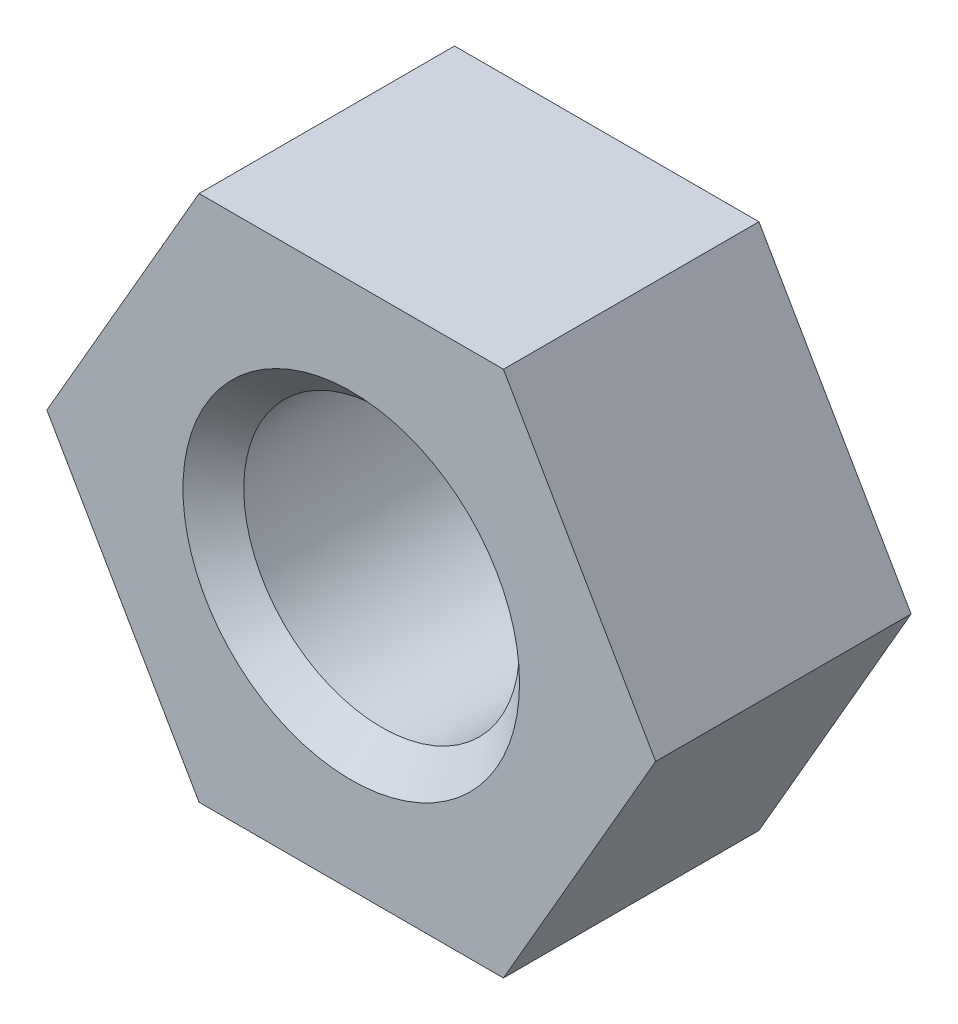
SolidWorks part; units mm, degrees
ref_plane "Front Plane" through (0, 0, 0) normal (0, 0, 1) x (1, 0, 0)
ref_plane "Top Plane" through (0, 0, 0) normal (0, 1, 0) x (1, 0, 0)
ref_plane "Right Plane" through (0, 0, 0) normal (1, 0, 0) x (0, 0, -1)
sketch "Sketch1" plane through (0, 0, 0) normal (0, 0, 1) x (1, 0, 0)
  line L1 (7.5056, 0) -> (3.7528, 6.5)
  line L2 (3.7528, 6.5) -> (-3.7528, 6.5)
  line L3 (-3.7528, 6.5) -> (-7.5056, 0)
  line L4 (-7.5056, 0) -> (-3.7528, -6.5)
  line L5 (-3.7528, -6.5) -> (3.7528, -6.5)
  line L6 (3.7528, -6.5) -> (7.5056, 0)
  circle A0 centre (0, 0) radius 6.5 construction
  circle A1 centre (0, 0) radius 3.4
  dimension "D2" = 6.8
  dimension "D1" = 13
extrude "Boss-Extrude1" add sketch "Sketch1" along normal blind 6.3
chamfer "Chamfer1" distance 0.75 angle 45 2 edges at (3.4, 0, 0) (3.4, 0, 6.3)
